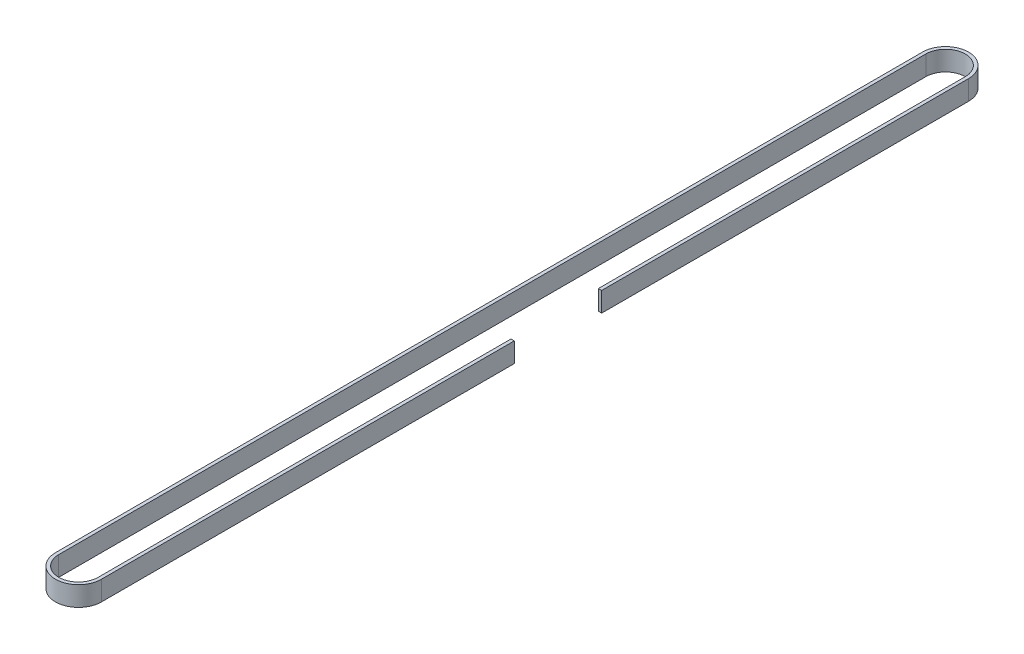
SolidWorks part; units mm, degrees
material "Caucho"
ref_plane "Alzado" through (0, 0, 0) normal (0, 0, 1) x (1, 0, 0)
ref_plane "Planta" through (0, 0, 0) normal (0, 1, 0) x (1, 0, 0)
ref_plane "Vista lateral" through (0, 0, 0) normal (1, 0, 0) x (0, 0, -1)
sketch "Sketch2" plane through (0, 0, 0) normal (0, 1, 0) x (1, 0, 0)
  line L0 (0, -276.0046) -> (0, 13524.226) construction
  line L1 (-6, -125) -> (-6, 139)
  line L2 (6, -125) -> (6, 0.6955)
  line L3 (6, 27.3045) -> (6, 139)
  line L4 (6, 0.6955) -> (6, 27.3045) construction
  line L5 (7, 27.3045) -> (7, 139)
  line L6 (-7, -125) -> (-7, 139)
  line L7 (7, -125) -> (7, 0.6955)
  line L8 (7, 0.6955) -> (6, 0.6955)
  line L9 (7, 27.3045) -> (6, 27.3045)
  arc A0 (-6, 139) -> (6, 139) centre (0, 139) cw
  arc A1 (6, -125) -> (-6, -125) centre (0, -125) cw
  arc A2 (-7, 139) -> (7, 139) centre (0, 139) cw
  arc A3 (7, -125) -> (-7, -125) centre (0, -125) cw
  point P1 (0, 0)
  point P4 (0, 0)
  point P5 (0, 0)
  dimension "D1" = 6
  dimension "D2" = 264
extrude "Boss-Extrude1" add sketch "Sketch2" along normal blind 6
